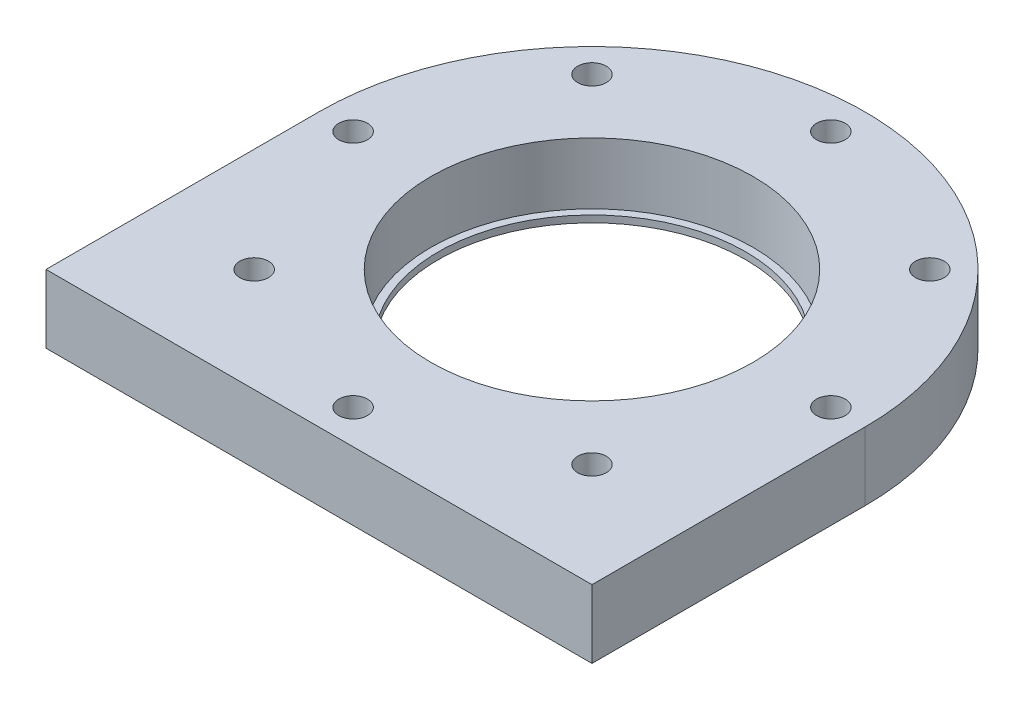
SolidWorks part; units mm, degrees
ref_plane "前视基准面" through (0, 0, 0) normal (0, 0, 1) x (1, 0, 0)
ref_plane "上视基准面" through (0, 0, 0) normal (0, 1, 0) x (1, 0, 0)
ref_plane "右视基准面" through (0, 0, 0) normal (1, 0, 0) x (0, 0, -1)
other "Configuration Table"
sketch "草图1" plane through (0, 0, 0) normal (0, 1, 0) x (1, 0, 0)
  line L2 (-40, 0) -> (-40, -40)
  line L3 (-40, -40) -> (40, -40)
  line L4 (40, 0) -> (40, -40)
  arc A0 (40, 0) -> (-40, 0) centre (0, 0) ccw
  circle A1 centre (0, 0) radius 22.5
  dimension "D1" = 80
  dimension "D2" = 45
extrude "凸台-拉伸1" add sketch "草图1" along normal blind 10
sketch "草图2" plane through (0, 10, 0) normal (0, 1, 0) x (1, 0, 0)
  circle A0 centre (0, 0) radius 35 construction
  circle A1 centre (0, 35) radius 2.1
  circle A2 centre (24.7487, 24.7487) radius 2.1
  circle A3 centre (35, 0) radius 2.1
  circle A4 centre (24.7487, -24.7487) radius 2.1
  circle A5 centre (0, -35) radius 2.1
  circle A6 centre (-24.7487, -24.7487) radius 2.1
  circle A7 centre (-35, 0) radius 2.1
  circle A8 centre (-24.7487, 24.7487) radius 2.1
  point P21 (0, 0)
  dimension "D1" = 70
  dimension "D2" = 4.2
  dimension "D3" = 8
extrude "切除-拉伸1" cut sketch "草图2" against normal through all
sketch "草图5" plane through (0, 10, 0) normal (0, 1, 0) x (1, 0, 0)
  circle A0 centre (0, 0) radius 23.6
  dimension "D1" = 47.2
extrude "切除-拉伸2" cut sketch "草图5" against normal blind 9
